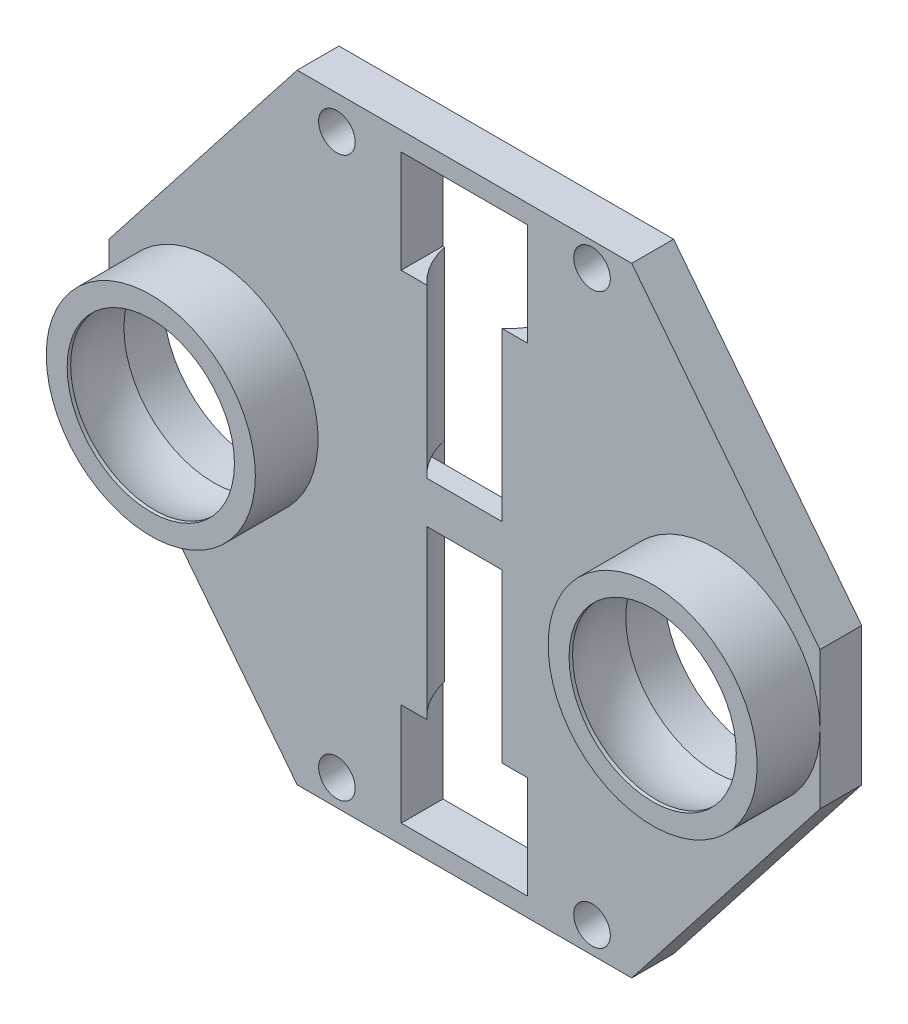
SolidWorks part; units mm, degrees
ref_plane "Alzado" through (0, 0, 0) normal (0, 0, 1) x (1, 0, 0)
ref_plane "Planta" through (0, 0, 0) normal (0, 1, 0) x (1, 0, 0)
ref_plane "Vista lateral" through (0, 0, 0) normal (1, 0, 0) x (0, 0, -1)
sketch "Croquis1" plane through (0, 0, 0) normal (0, 0, 1) x (1, 0, 0)
  line L1 (0, 0) -> (22, 0)
  line L2 (0, 0) -> (0, 55.2)
  line L3 (0, 55.2) -> (22, 55.2)
  line L4 (22, 0) -> (22, 55.2)
  dimension "D1" = 55.2
  dimension "D2" = 22
extrude "Saliente-Extruir1" add sketch "Croquis1" along normal blind 4
sketch "Croquis2" plane through (0, 55.2, 0) normal (0, 1, 0) x (1, 0, 0)
  line L0 (22, 0) -> (0, 0) construction
  line L1 (4.95, 0) -> (17.05, 0)
  line L2 (4.95, 0) -> (4.95, -4)
  line L3 (4.95, -4) -> (17.05, -4)
  line L4 (17.05, 0) -> (17.05, -4)
  line L5 (22, -4) -> (0, -4) construction
  line L6 (0, -4) -> (0, 0) construction
  dimension "D1" = 12.1
  dimension "D2" = 4.95
extrude "Cortar-Extruir1" cut sketch "Croquis2" against normal blind 9.6
sketch "Croquis3" plane through (0, 0, 0) normal (0, -1, 0) x (1, 0, 0)
  line L0 (0, 4) -> (22, 4) construction
  line L1 (4.95, 4) -> (17.05, 4)
  line L2 (4.95, 4) -> (4.95, 0)
  line L3 (4.95, 0) -> (17.05, 0)
  line L4 (17.05, 4) -> (17.05, 0)
  line L5 (0, 0) -> (22, 0) construction
  line L6 (0, 4) -> (0, 0) construction
  line L7 (22, 4) -> (22, 0) construction
  dimension "D1" = 4.95
  dimension "D2" = 4.95
extrude "Cortar-Extruir2" cut sketch "Croquis3" against normal blind 9.6
sketch "Croquis5" plane through (0, 9.6, 0) normal (0, -1, 0) x (1, 0, 0)
  line L0 (7.4, 4) -> (14.6, 4)
  line L1 (17.05, 4) -> (4.95, 4) construction
  line L2 (4.95, -1.5) -> (17.05, -1.5)
  arc A2 (7.4, 4) -> (4.95, -1.5) centre (12.4499, -1.5452) ccw
  arc A3 (17.05, -1.5) -> (14.6, 4) centre (9.5501, -1.5452) ccw
  dimension "D1" = 7.2
  dimension "D2" = 2.45
extrude "Cortar-Extruir3" cut sketch "Croquis5" against normal blind 16
sketch "Croquis7" plane through (0, 45.6, 0) normal (0, 1, 0) x (1, 0, 0)
  line L5 (4.95, -4) -> (17.05, -4) construction
  line L11 (4.95, 1.5) -> (17.05, 1.5)
  line L12 (7.4, -4) -> (14.6, -4)
  arc A3 (4.95, 1.5) -> (7.4, -4) centre (12.4499, 1.5452) ccw
  arc A4 (14.6, -4) -> (17.05, 1.5) centre (9.5501, 1.5452) ccw
extrude "Cortar-Extruir4" cut sketch "Croquis7" against normal blind 16
sketch "Croquis9" plane through (0, 0, 0) normal (0, 0, -1) x (-1, 0, 0)
  line L1 (-16.8892, 29.6) -> (-5.1108, 29.6)
  line L2 (-16.8892, 29.6) -> (-16.8892, 25.6)
  line L3 (-16.8892, 25.6) -> (-5.1108, 25.6)
  line L4 (-5.1108, 29.6) -> (-5.1108, 25.6)
extrude "Cortar-Extruir5" cut sketch "Croquis9" against normal blind 2
sketch "Croquis11" plane through (0, 55.2, 0) normal (0, 1, 0) x (1, 0, 0)
  line L0 (0, -4) -> (4.95, -4) construction
  line L1 (4.95, -4) -> (4.95, 0) construction
  line L2 (4.95, 0) -> (0, 0) construction
  line L3 (0, 0) -> (0, -4) construction
  line L4 (22, 0) -> (17.05, 0) construction
  line L5 (17.05, 0) -> (17.05, -4) construction
  line L6 (17.05, -4) -> (22, -4) construction
  line L7 (22, -4) -> (22, 0) construction
  line L8 (0, -4) -> (4.95, -4)
  line L9 (4.95, -4) -> (4.95, 0)
  line L10 (4.95, 0) -> (0, 0)
  line L11 (0, 0) -> (0, -4)
  line L12 (22, 0) -> (17.05, 0)
  line L13 (17.05, 0) -> (17.05, -4)
  line L14 (17.05, -4) -> (22, -4)
  line L15 (22, -4) -> (22, 0)
extrude "Saliente-Extruir3" add sketch "Croquis11" along normal blind 2
sketch "Croquis12" plane through (4.95, 0, 0) normal (1, 0, 0) x (0, 0, -1)
  line L0 (-4, 57.2) -> (0, 57.2)
  line L1 (0, 57.2) -> (0, 55.4)
  line L2 (0, 45.6) -> (0, 57.2) construction
  line L3 (0, 55.4) -> (-4, 55.4)
  line L4 (-4, 45.6) -> (-4, 57.2) construction
  line L5 (-4, 55.4) -> (-4, 57.2)
extrude "Saliente-Extruir4" add sketch "Croquis12" along normal blind 12.1
sketch "Croquis13" plane through (0, 0, 0) normal (0, -1, 0) x (1, 0, 0)
  line L0 (22, 4) -> (17.05, 4) construction
  line L1 (17.05, 4) -> (17.05, 0) construction
  line L2 (17.05, 0) -> (22, 0) construction
  line L3 (22, 0) -> (22, 4) construction
  line L4 (0, 0) -> (4.95, 0) construction
  line L5 (4.95, 0) -> (4.95, 4) construction
  line L6 (4.95, 4) -> (0, 4) construction
  line L7 (0, 4) -> (0, 0) construction
  line L8 (22, 4) -> (17.05, 4)
  line L9 (17.05, 4) -> (17.05, 0)
  line L10 (17.05, 0) -> (22, 0)
  line L11 (22, 0) -> (22, 4)
  line L12 (0, 0) -> (4.95, 0)
  line L13 (4.95, 0) -> (4.95, 4)
  line L14 (4.95, 4) -> (0, 4)
  line L15 (0, 4) -> (0, 0)
extrude "Saliente-Extruir5" add sketch "Croquis13" along normal blind 2
sketch "Croquis14" plane through (4.95, 0, 0) normal (1, 0, 0) x (0, 0, -1)
  line L0 (-4, 9.6) -> (-4, -2) construction
  line L1 (0, -2) -> (-4, -2)
  line L2 (0, -2) -> (0, -0.2)
  line L3 (0, -0.2) -> (-4, -0.2)
  line L4 (-4, -2) -> (-4, -0.2)
extrude "Saliente-Extruir6" add sketch "Croquis14" along normal blind 12.1
sketch "Croquis17" plane through (0, 0, 0) normal (-1, 0, 0) x (0, 0, 1)
  line L4 (0, 57.2) -> (0, -2)
  line L5 (0, -2) -> (4, -2)
  line L6 (4, -2) -> (4, 57.2)
  line L7 (4, 57.2) -> (0, 57.2)
  line L8 (0, 57.2) -> (0, -2)
  line L10 (4, -2) -> (4, 57.2)
  line L11 (4, 57.2) -> (0, 57.2)
  line L13 (0, -2) -> (4, -2)
  dimension "D1" = 0
extrude "Saliente-Extruir8" add sketch "Croquis17" along normal blind 23 contours L8 L13 L10 L11
sketch "Croquis18" plane through (22, 0, 0) normal (1, 0, 0) x (0, 0, -1)
  line L4 (0, -2) -> (0, 57.2)
  line L5 (0, 57.2) -> (-4, 57.2)
  line L6 (-4, 57.2) -> (-4, -2)
  line L7 (-4, -2) -> (0, -2)
  line L8 (0, -2) -> (0, 57.2)
  line L9 (0, 57.2) -> (-4, 57.2)
  line L10 (-4, 57.2) -> (-4, -2)
  line L11 (-4, -2) -> (0, -2)
  dimension "D1" = 0
extrude "Saliente-Extruir9" add sketch "Croquis18" along normal blind 23
sketch "Croquis19" plane through (0, 0, 0) normal (0, 0, -1) x (-1, 0, 0)
  line L0 (23, -2) -> (-45, -2) construction
  line L5 (23, 57.2) -> (23, -2) construction
  circle A0 centre (-23.2, 54.9) radius 1.75
  circle A1 centre (1.2, 54) radius 1.75
  circle A2 centre (1.2, 0.5) radius 1.75
  circle A3 centre (-23.2, 0.5) radius 1.75
  dimension "D1" = 3.5
  dimension "D2" = 3.5
  dimension "D3" = 3.5
  dimension "D4" = 3.5
  dimension "D5" = 2.5
  dimension "D6" = 2.5
  dimension "D7" = 54.4
  dimension "D8" = 21.8
  dimension "D9" = 24.4
  dimension "D10" = 24.4
  dimension "D12" = 21.8
extrude "Cortar-Extruir6" cut sketch "Croquis19" against normal blind 11.5
sketch "Croquis20" plane through (0, 0, 0) normal (0, 0, -1) x (-1, 0, 0)
  line L0 (23, 27.6) -> (-38.1967, 27.6) construction
  line L1 (23, 57.2) -> (23, -2) construction
  line L2 (-45, -2) -> (-45, 57.2) construction
  circle A0 centre (13, 27.6) radius 8.8
  circle A1 centre (-35, 27.6) radius 8.901
  dimension "D1" = 10
  dimension "D2" = 10
extrude "Cortar-Extruir7" cut sketch "Croquis20" against normal blind 4
sketch "Croquis21" plane through (0, 0, 0) normal (0, 0, -1) x (-1, 0, 0)
  line L0 (-45, 57.2) -> (-45, 34.2)
  line L1 (-45, -2) -> (-45, 57.2) construction
  line L2 (-45, 57.2) -> (-27, 57.2)
  line L3 (-45, 57.2) -> (23, 57.2) construction
  line L4 (-45, -2) -> (-45, 21)
  line L5 (-45, -2) -> (-27, -2)
  line L6 (23, -2) -> (-45, -2) construction
  line L7 (23, 57.2) -> (23, 34.2)
  line L8 (23, 57.2) -> (23, -2) construction
  line L9 (23, 57.2) -> (5, 57.2)
  line L10 (23, -2) -> (23, 21)
  line L11 (23, -2) -> (5, -2)
  line L12 (5, -2) -> (23, 21)
  line L13 (23, 34.2) -> (5, 57.2)
  line L14 (-27, 57.2) -> (-45, 34.2)
  line L15 (-45, 21) -> (-27, -2)
extrude "Cortar-Extruir8" cut sketch "Croquis21" against normal blind 10
sketch "Croquis22" plane through (0, 0, 4) normal (0, 0, 1) x (1, 0, 0)
  circle A0 centre (-13, 27.6) radius 8
  circle A1 centre (35, 27.6) radius 8
  circle A2 centre (35, 27.6) radius 10
  circle A3 centre (-13, 27.6) radius 10
extrude "Saliente-Extruir10" add sketch "Croquis22" along normal blind 6
ref_plane "Plano1" through (0, 0, 6) normal (0, 0, 1) x (1, 0, 0)
sketch "Croquis23" plane through (0, 0, 6) normal (0, 0, 1) x (1, 0, 0)
  line L0 (43.8, 27.6) -> (26.2, 27.6)
  arc A0 (43.8, 27.6) -> (26.2, 27.6) centre (35, 27.6) ccw
revolve "Cortar-Revolución1" cut sketch "Croquis23" angle 360 about L0
sketch "Croquis24" plane through (0, 0, 6) normal (0, 0, 1) x (1, 0, 0)
  line L0 (-13, 36.4) -> (-13, 18.8)
  arc A0 (-13, 36.4) -> (-13, 18.8) centre (-13, 27.6) ccw
revolve "Cortar-Revolución2" cut sketch "Croquis24" angle 360 about L0
